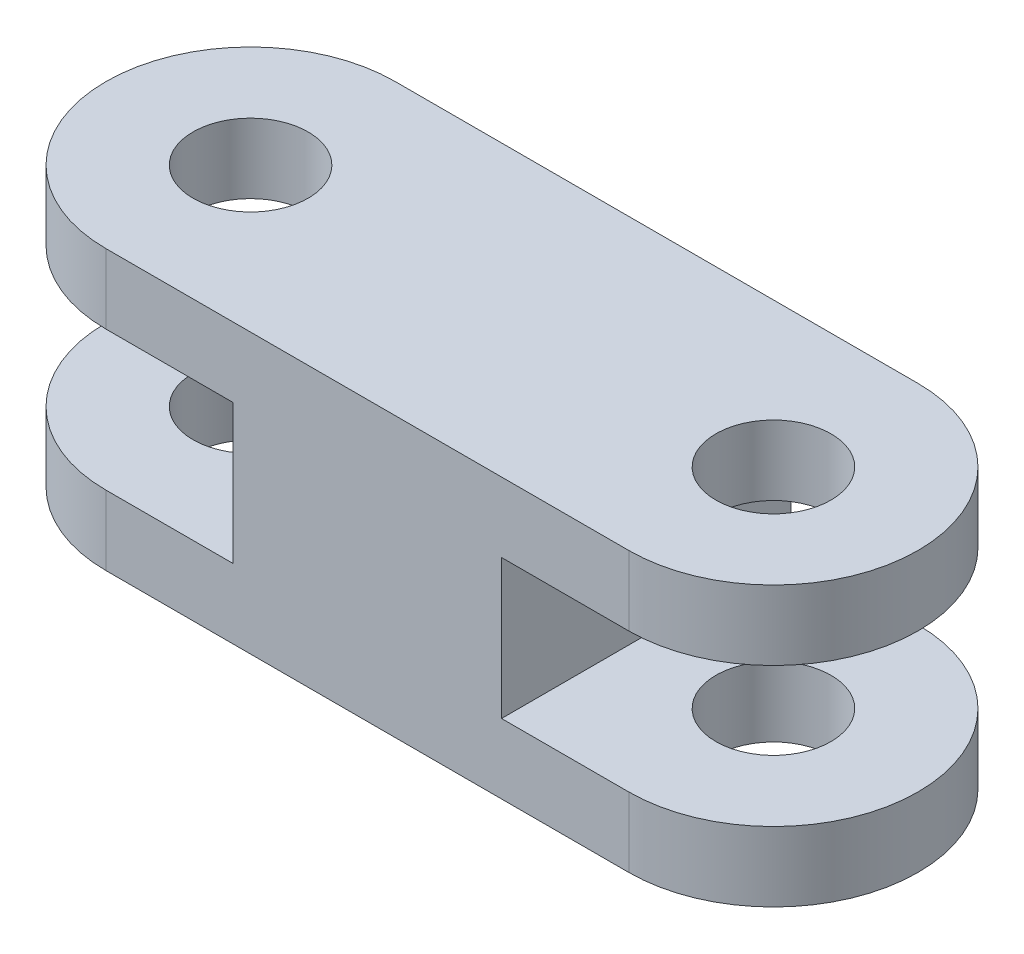
SolidWorks part; units mm, degrees
ref_plane "Front Plane" through (0, 0, 0) normal (0, 0, 1) x (1, 0, 0)
ref_plane "Top Plane" through (0, 0, 0) normal (0, 1, 0) x (1, 0, 0)
ref_plane "Right Plane" through (0, 0, 0) normal (1, 0, 0) x (0, 0, -1)
sketch "Sketch1" plane through (0, 0, 0) normal (0, 1, 0) x (1, 0, 0)
  line L0 (-7.5, 0) -> (7.5, 0) construction
  line L1 (-55, 0) -> (55, 0) construction
  line L2 (-7.5, 4.15) -> (7.5, 4.15)
  line L3 (-7.5, -4.15) -> (7.5, -4.15)
  arc A0 (-7.5, 4.15) -> (-7.5, -4.15) centre (-7.5, 0) ccw
  arc A1 (7.5, -4.15) -> (7.5, 4.15) centre (7.5, 0) ccw
  circle A2 centre (-7.5, 0) radius 1.65
  circle A3 centre (7.5, 0) radius 1.65
  point P5 (0, 0)
  dimension "D1" = 3.3
  dimension "D2" = 2.5
  dimension "D4" = 3.3
  dimension "D3" = 15
extrude "Boss-Extrude1" add sketch "Sketch1" along normal blind 2
sketch "Sketch2" plane through (0, 2, 0) normal (0, 1, 0) x (1, 0, 0)
  line L0 (7.5, 4.15) -> (-7.5, 4.15) construction
  line L1 (3.85, -4.15) -> (-3.85, -4.15)
  line L2 (3.85, -4.15) -> (3.85, 4.15)
  line L3 (3.85, 4.15) -> (-3.85, 4.15)
  line L4 (-3.85, -4.15) -> (-3.85, 4.15)
  line L5 (3.85, -4.15) -> (-3.85, 4.15) construction
  line L6 (3.85, 4.15) -> (-3.85, -4.15) construction
  circle A0 centre (-7.5, 0) radius 1.65 construction
  point P0 (0, 0)
  dimension "D1" = 3.65
extrude "Boss-Extrude2" add sketch "Sketch2" along normal blind 1
mirror "Mirror1" about plane through (0, 3, 0) normal (0, 1, 0) of "Boss-Extrude2", "Boss-Extrude1"
ref_plane "Plane1" through (0, 4, 0) normal (0, 1, 0) x (1, 0, 0)
mirror "Mirror4" about plane through (0, 4, 0) normal (0, -1, 0) of bodies 108
